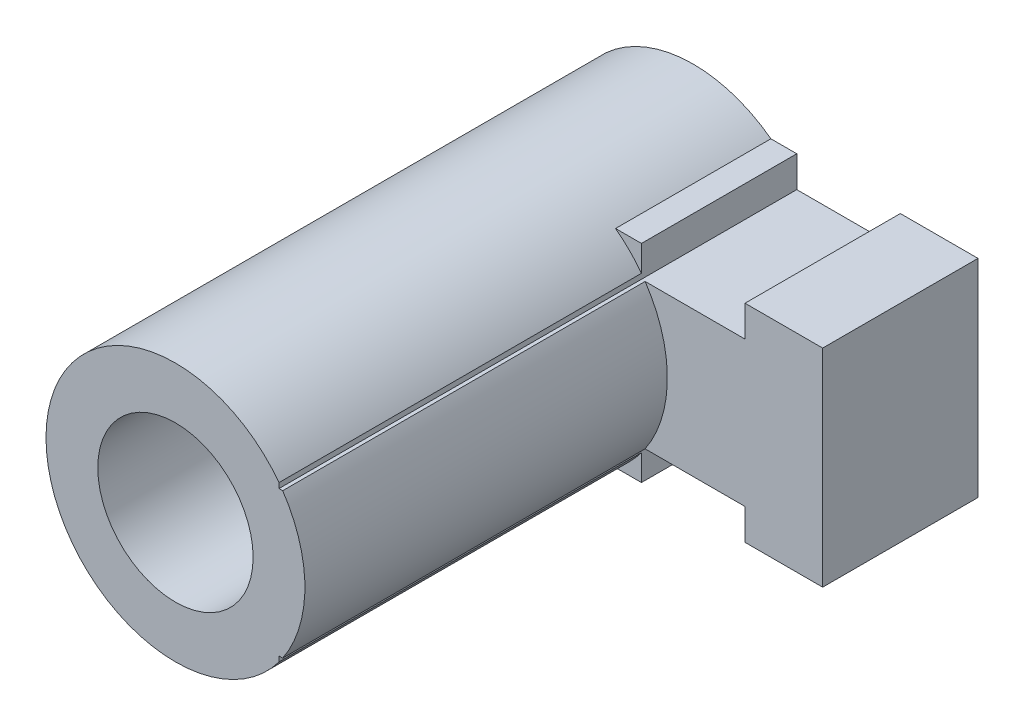
SolidWorks part; units mm, degrees
ref_plane "前视基准面" through (0, 0, 0) normal (0, 0, 1) x (1, 0, 0)
ref_plane "上视基准面" through (0, 0, 0) normal (0, 1, 0) x (1, 0, 0)
ref_plane "右视基准面" through (0, 0, 0) normal (1, 0, 0) x (0, 0, -1)
sketch "草图1" plane through (0, 0, 0) normal (0, 0, 1) x (1, 0, 0)
  circle A0 centre (0, 0) radius 2.5
  circle A1 centre (0, 0) radius 1.5
  dimension "D1" = 5
extrude "凸台-拉伸1" add sketch "草图1" along normal blind 10
sketch "草图2" plane through (0, 0, 0) normal (0, 0, -1) x (-1, 0, 0)
  line L1 (-1.5, -2) -> (-5.5, -2)
  line L2 (-1.5, -2) -> (-1.5, 2)
  line L3 (-1.5, 2) -> (-5.5, 2)
  line L4 (-5.5, -2) -> (-5.5, 2)
  point P6 (0.4018, 0.519)
  dimension "D1" = 4
  dimension "D2" = 4
  dimension "D3" = 2
  dimension "D4" = 5.5
extrude "凸台-拉伸2" add sketch "草图2" against normal blind 3
sketch "草图3" plane through (0, 0, 0) normal (0, 0, -1) x (-1, 0, 0)
  line L0 (-1.5, 2) -> (-5.5, 2) construction
  line L1 (-4, -2) -> (-2, -2)
  line L2 (-4, -2) -> (-4, -1.4)
  line L3 (-4, -1.4) -> (-2, -1.4)
  line L4 (-2, -2) -> (-2, -1.4)
  line L5 (-4, 2) -> (-2, 2)
  line L6 (-4, 2) -> (-4, 1.4)
  line L7 (-4, 1.4) -> (-2, 1.4)
  line L8 (-2, 2) -> (-2, 1.4)
  line L9 (-5.5, -2) -> (-1.5, -2) construction
  line L10 (-5.5, 2) -> (-5.5, -2) construction
  dimension "D1" = 0.6
  dimension "D2" = 0.6
  dimension "D3" = 0
  dimension "D4" = 2
  dimension "D5" = 2
  dimension "D6" = 0
  dimension "D7" = 1.5
  dimension "D8" = 1.5
extrude "切除-拉伸1" cut sketch "草图3" against normal through all
